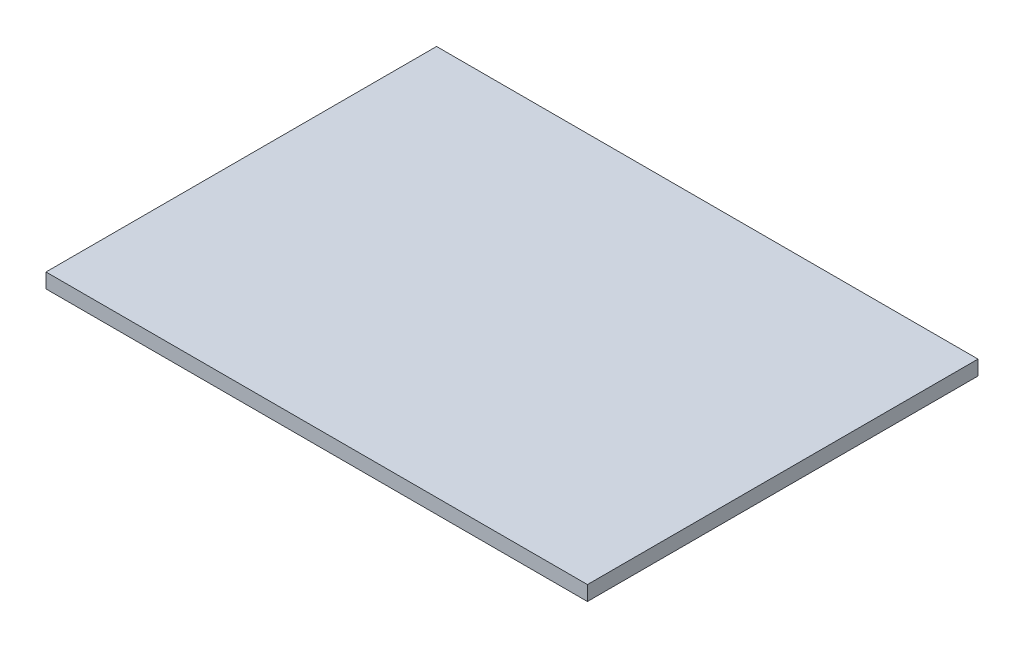
SolidWorks part; units mm, degrees
ref_plane "Front Plane" through (0, 0, 0) normal (0, 0, 1) x (1, 0, 0)
ref_plane "Top Plane" through (0, 0, 0) normal (0, 1, 0) x (1, 0, 0)
ref_plane "Right Plane" through (0, 0, 0) normal (1, 0, 0) x (0, 0, -1)
sketch "Sketch1" plane through (0, 0, 0) normal (0, 1, 0) x (1, 0, 0)
  line L1 (0, 0) -> (-26.7, 0)
  line L2 (0, 0) -> (0, 19.26)
  line L3 (0, 19.26) -> (-26.7, 19.26)
  line L4 (-26.7, 0) -> (-26.7, 19.26)
  dimension "D1" = 26.7
  dimension "D2" = 19.26
extrude "Boss-Extrude2" add sketch "Sketch1" along normal blind 0.725
